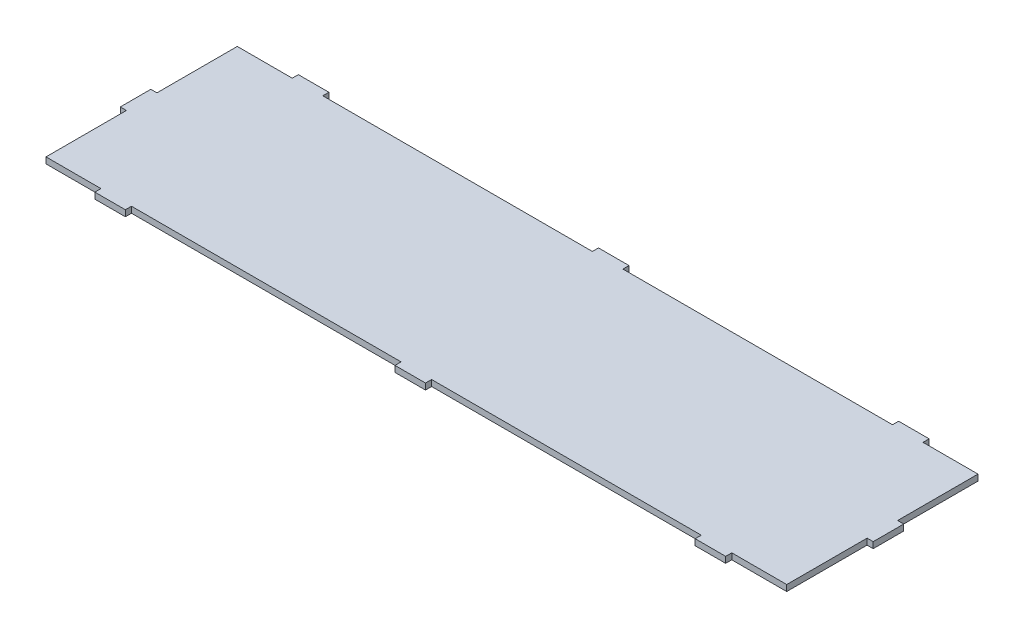
SolidWorks part; units mm, degrees
ref_plane "Front Plane" through (0, 0, 0) normal (0, 0, 1) x (1, 0, 0)
ref_plane "Top Plane" through (0, 0, 0) normal (0, 1, 0) x (1, 0, 0)
ref_plane "Right Plane" through (0, 0, 0) normal (1, 0, 0) x (0, 0, -1)
sketch "Sketch1" plane through (0, 0, 0) normal (0, 1, 0) x (1, 0, 0)
  line L0 (340, -100) -> (340, -97)
  line L6 (192.5, -97) -> (192.5, -100)
  line L8 (325, -97) -> (325, -100)
  line L10 (45, -97) -> (45, -100)
  line L12 (177.5, -97) -> (177.5, -100)
  line L13 (30, -100) -> (30, -97)
  line L15 (30, 0) -> (30, -3)
  line L16 (177.5, -3) -> (177.5, 0)
  line L18 (45, -3) -> (45, 0)
  line L19 (325, -3) -> (325, 0)
  line L21 (192.5, -3) -> (192.5, 0)
  line L23 (340, 0) -> (340, -3)
  line L26 (367, -57.5) -> (370, -57.5)
  line L27 (367, -42.5) -> (370, -42.5)
  line L28 (3, -42.5) -> (0, -42.5)
  line L29 (3, -57.5) -> (0, -57.5)
  line L38 (3, -42.5) -> (3, -3)
  line L39 (3, -57.5) -> (3, -97)
  line L40 (0, -42.5) -> (0, -57.5)
  line L41 (370, -42.5) -> (370, -57.5)
  line L42 (367, -42.5) -> (367, -3)
  line L43 (367, -57.5) -> (367, -97)
  line L44 (3, -3) -> (30, -3)
  line L45 (3, -97) -> (30, -97)
  line L46 (30, 0) -> (45, 0)
  line L47 (177.5, 0) -> (192.5, 0)
  line L48 (325, 0) -> (340, 0)
  line L49 (340, -100) -> (325, -100)
  line L50 (192.5, -100) -> (177.5, -100)
  line L51 (45, -100) -> (30, -100)
  line L52 (45, -3) -> (177.5, -3)
  line L53 (192.5, -3) -> (325, -3)
  line L54 (340, -3) -> (367, -3)
  line L55 (45, -97) -> (177.5, -97)
  line L56 (192.5, -97) -> (325, -97)
  line L57 (340, -97) -> (367, -97)
  point P20 (185, -97)
  point P35 (185, -3)
  dimension "D1" = 15
  dimension "D2" = 15
  dimension "D3" = 7.5
  dimension "D4" = 15
  dimension "D5" = 3
  dimension "D6" = 3
  dimension "D7" = 3
  dimension "D8" = 370
  dimension "D9" = 15
  dimension "D10" = 3
extrude "Boss-Extrude1" add sketch "Sketch1" along normal blind 3
